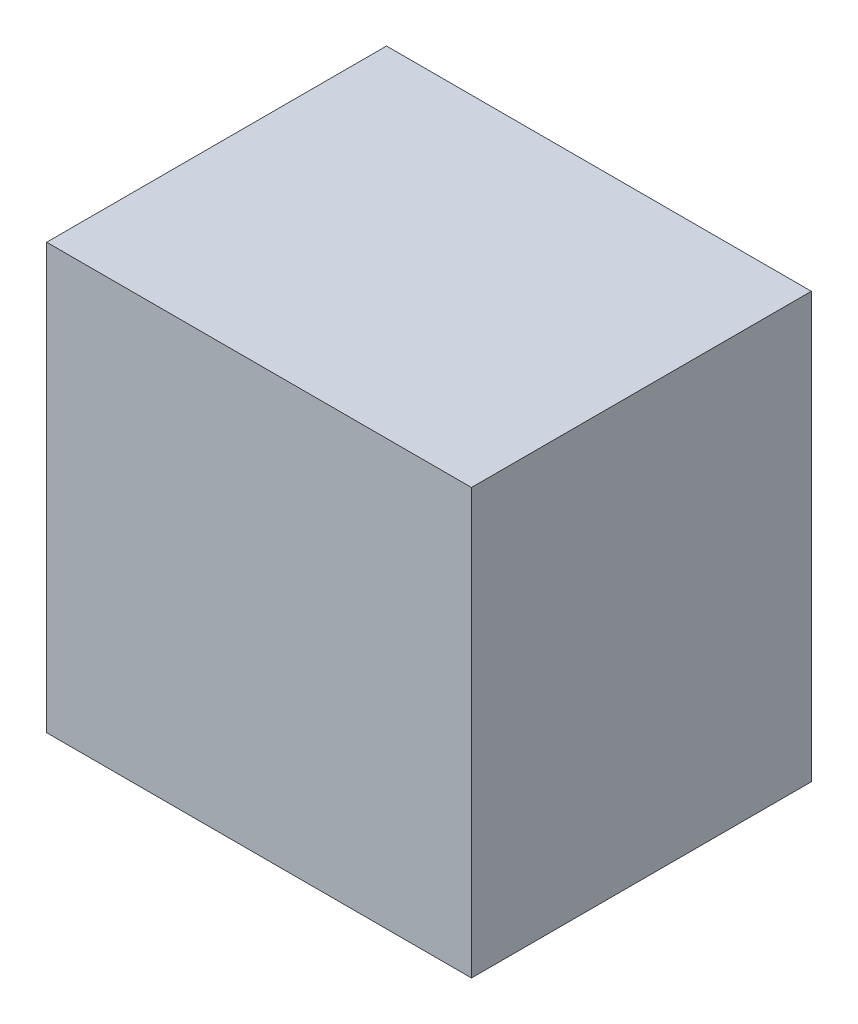
SolidWorks part; units mm, degrees
ref_plane "Front Plane" through (0, 0, 0) normal (0, 0, 1) x (1, 0, 0)
ref_plane "Top Plane" through (0, 0, 0) normal (0, 1, 0) x (1, 0, 0)
ref_plane "Right Plane" through (0, 0, 0) normal (1, 0, 0) x (0, 0, -1)
sketch "Sketch1" plane through (0, 0, 0) normal (0, 0, 1) x (1, 0, 0)
  line L1 (-12.5, -12.5) -> (12.5, -12.5)
  line L2 (-12.5, -12.5) -> (-12.5, 12.5)
  line L3 (-12.5, 12.5) -> (12.5, 12.5)
  line L4 (12.5, -12.5) -> (12.5, 12.5)
  line L5 (-12.5, -12.5) -> (12.5, 12.5) construction
  line L6 (-12.5, 12.5) -> (12.5, -12.5) construction
extrude "Boss-Extrude1" add sketch "Sketch1" along normal blind 20
